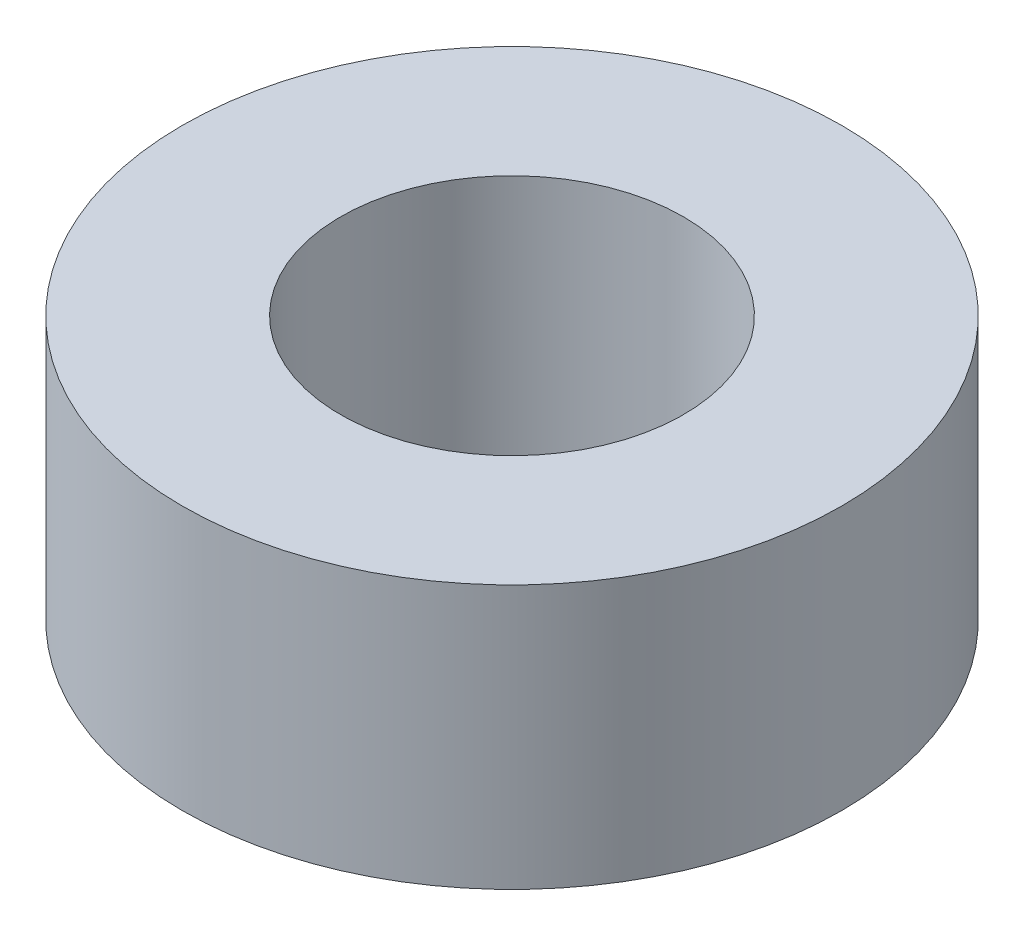
SolidWorks part; units mm, degrees
ref_plane "Front Plane" through (0, 0, 0) normal (0, 0, 1) x (1, 0, 0)
ref_plane "Top Plane" through (0, 0, 0) normal (0, 1, 0) x (1, 0, 0)
ref_plane "Right Plane" through (0, 0, 0) normal (1, 0, 0) x (0, 0, -1)
sketch "Sketch1" plane through (0, 0, 0) normal (0, 1, 0) x (1, 0, 0)
  circle A0 centre (0, 0) radius 9.525
  circle A1 centre (0, 0) radius 4.953
  dimension "D1" = 19.05
  dimension "D2" = 9.906
extrude "Boss-Extrude1" add sketch "Sketch1" along normal blind 7.62
